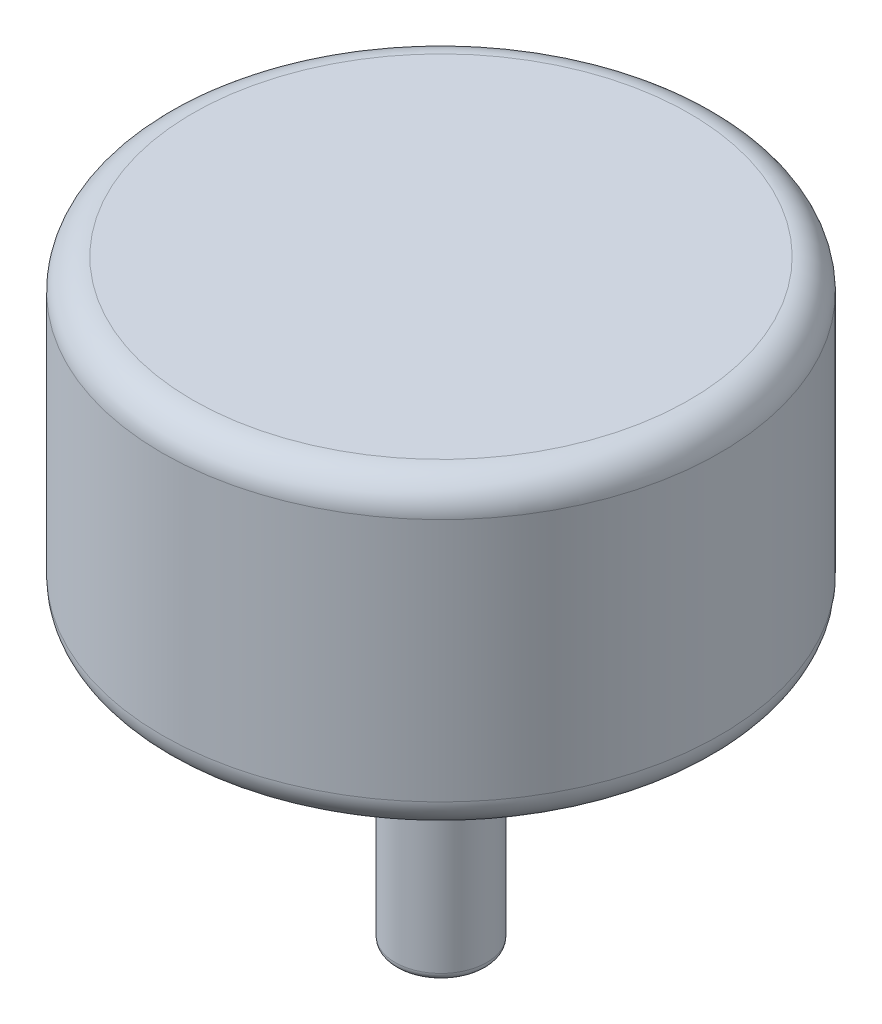
SolidWorks part; units mm, degrees
ref_plane "前视基准面" through (0, 0, 0) normal (0, 0, 1) x (1, 0, 0)
ref_plane "上视基准面" through (0, 0, 0) normal (0, 1, 0) x (1, 0, 0)
ref_plane "右视基准面" through (0, 0, 0) normal (1, 0, 0) x (0, 0, -1)
sketch "草图1" plane through (0, 0, 0) normal (0, 1, 0) x (1, 0, 0)
  circle A0 centre (0, 0) radius 18.25
  dimension "D1" = 36.5
extrude "凸台-拉伸1" add sketch "草图1" along normal blind 20
fillet "圆角1" radius 2 2 edges at (0, 0, 18.25) (0, 20, 18.25)
sketch "草图2" plane through (0, 0, 0) normal (0, 1, 0) x (1, 0, 0)
  circle A0 centre (0, 0) radius 10
  dimension "D1" = 20
extrude "凸台-拉伸2" add sketch "草图2" against normal blind 1.6
sketch "草图3" plane through (0, 0, 0) normal (0, 1, 0) x (1, 0, 0)
  circle A0 centre (0, 0) radius 3
  dimension "D1" = 6
extrude "凸台-拉伸3" add sketch "草图3" against normal blind 19
fillet "圆角2" radius 0.5 1 edges at (0, -19, 3)
